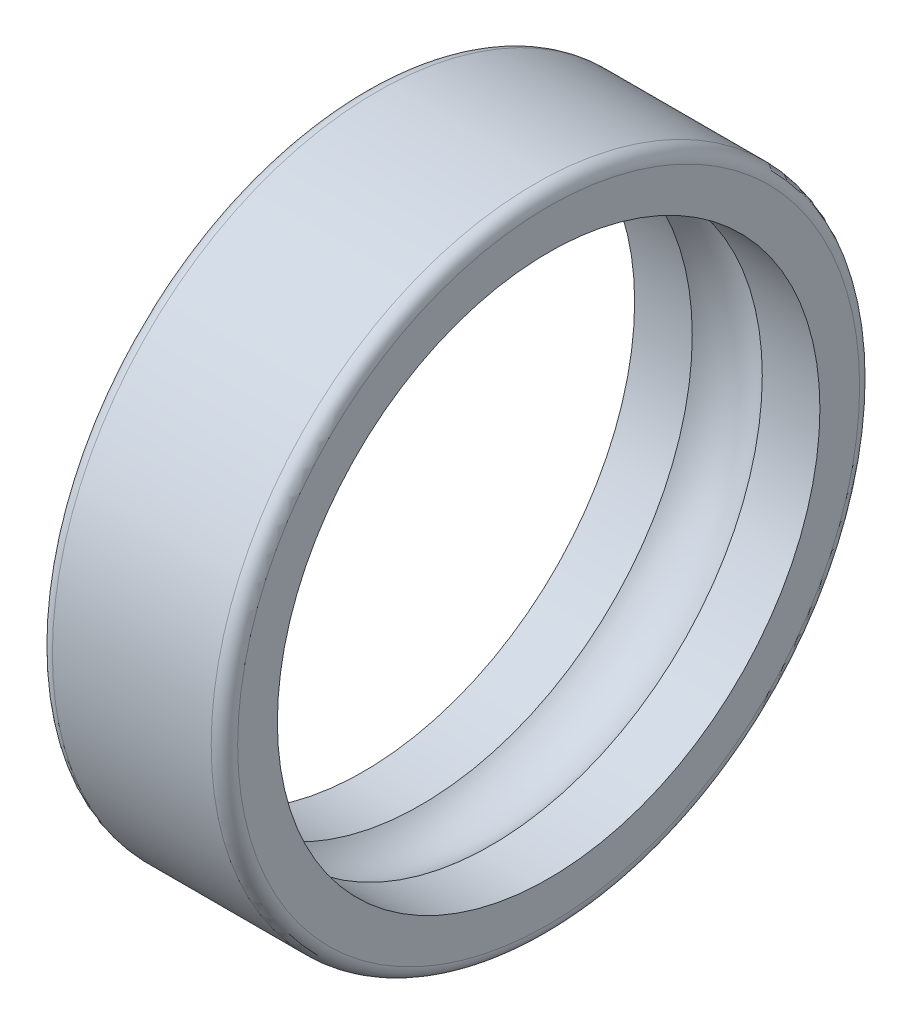
SolidWorks part; units mm, degrees
ref_plane "Plan1" through (0, 0, 0) normal (0, 0, 1) x (1, 0, 0)
ref_plane "Plan2" through (0, 0, 0) normal (0, 1, 0) x (1, 0, 0)
ref_plane "Plan3" through (0, 0, 0) normal (1, 0, 0) x (0, 0, -1)
sketch "Esquisse1" plane through (0, 0, 0) normal (0, 0, 1) x (1, 0, 0)
  line L0 (-5, 7.5) -> (-5, 17.5) construction
  line L1 (-4.2857, 17.5) -> (4.2857, 17.5)
  line L2 (-5, 16.7857) -> (-5, 14.6429)
  line L3 (-5, 14.6429) -> (-1.8898, 14.6429)
  line L4 (5, 16.7857) -> (5, 14.6429)
  line L5 (5, 7.5) -> (5, 17.5) construction
  line L6 (-5, 17.5) -> (5, 17.5) construction
  line L7 (1.8898, 14.6429) -> (5, 14.6429)
  line L8 (0, 0) -> (15, 0) construction
  line L9 (0, 0) -> (54, 0) construction
  arc A0 (4.2857, 17.5) -> (5, 16.7857) centre (4.2857, 16.7857) cw
  arc A1 (-4.2857, 17.5) -> (-5, 16.7857) centre (-4.2857, 16.7857) ccw
  arc A2 (1.8898, 14.6429) -> (-1.8898, 14.6429) centre (0, 12.5) ccw
  point P12 (5, 17.5)
  dimension "D2" = 0.7143
  dimension "D3" = 2.8571
  dimension "D1" = 2.8571
revolve "Base-Révolution" add sketch "Esquisse1" angle 360 about L8
